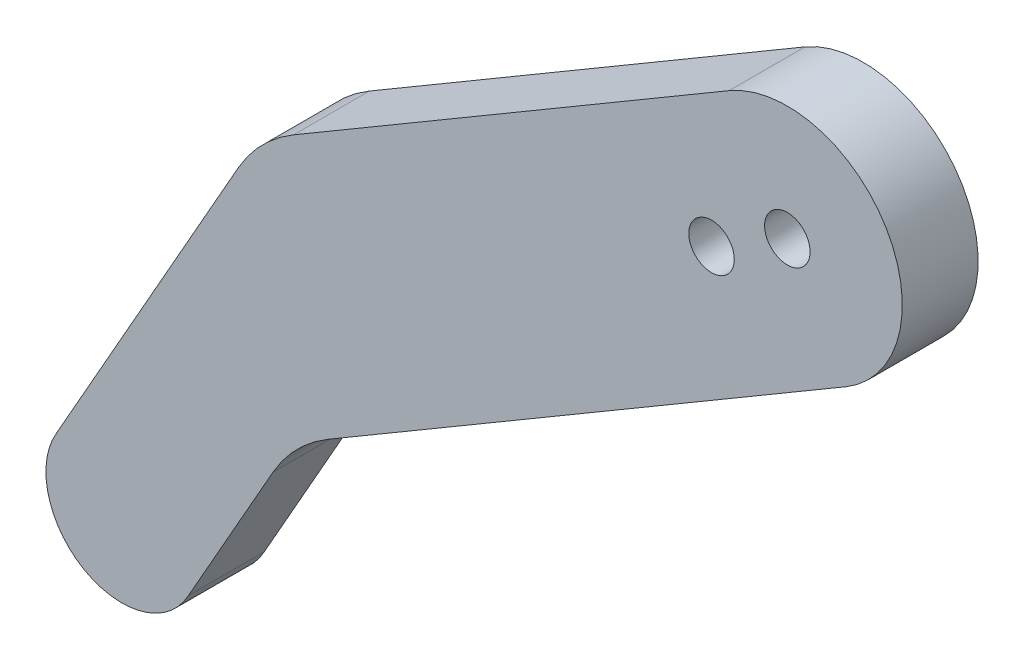
SolidWorks part; units mm, degrees
ref_plane "Front Plane" through (0, 0, 0) normal (0, 0, 1) x (1, 0, 0)
ref_plane "Top Plane" through (0, 0, 0) normal (0, 1, 0) x (1, 0, 0)
ref_plane "Right Plane" through (0, 0, 0) normal (1, 0, 0) x (0, 0, -1)
sketch "Sketch3" plane through (0, 0, 0) normal (0, 0, 1) x (1, 0, 0)
  line L0 (0, 0) -> (11.9948, 21.1568)
  line L1 (0, 0) -> (8.6992, -4.932) construction
  line L2 (8.6992, -4.932) -> (14.2824, 4.916)
  line L3 (15.6262, 24.8457) -> (44.3512, 41.7316)
  line L4 (44.3512, 41.7316) -> (52.034, 28.6623) construction
  line L5 (17.9139, 8.6048) -> (52.034, 28.6623)
  arc A0 (44.3512, 41.7316) -> (52.034, 28.6623) centre (48.1926, 35.1969) cw
  arc A1 (0, 0) -> (8.6992, -4.932) centre (4.3053, -2.5441) ccw
  arc A2 (11.9948, 21.1568) -> (15.6262, 24.8457) centre (20.694, 16.2249) cw
  arc A3 (14.2824, 4.916) -> (17.9139, 8.6048) centre (22.9816, -0.016) cw
  point P10 (13.3163, 23.4878)
  point P13 (19.9017, -5.697)
  point P15 (15.6039, 7.2469)
  dimension "D7" = 5.0008
  dimension "D8" = 10
  dimension "D9" = 10
  dimension "D1" = 27
  dimension "D2" = 36
  dimension "D3" = 150
  dimension "D5" = 14
  dimension "D6" = 10
extrude "Boss-Extrude1" add sketch "Sketch3" along normal blind 5 contours L0 A1 L2 L5 A0 L3
sketch "Sketch4" plane through (0, 0, 5) normal (0, 0, 1) x (1, 0, 0)
  line L0 (44.3512, 41.7316) -> (52.034, 28.6623) construction
  line L1 (48.1926, 35.1969) -> (23.4681, 20.6627) construction
  line L2 (44.3512, 41.7316) -> (52.034, 28.6623) construction
  circle A0 centre (48.1926, 35.1969) radius 1.5
  arc A1 (52.034, 28.6623) -> (44.3512, 41.7316) centre (48.1926, 35.1969) ccw construction
  circle A2 centre (43.1926, 32.2577) radius 1.5
  point P9 (48.1926, 35.1969)
  dimension "D1" = 3
  dimension "D2" = 5
  dimension "D3" = 3
extrude "Cut-Extrude1" cut sketch "Sketch4" against normal blind 7
